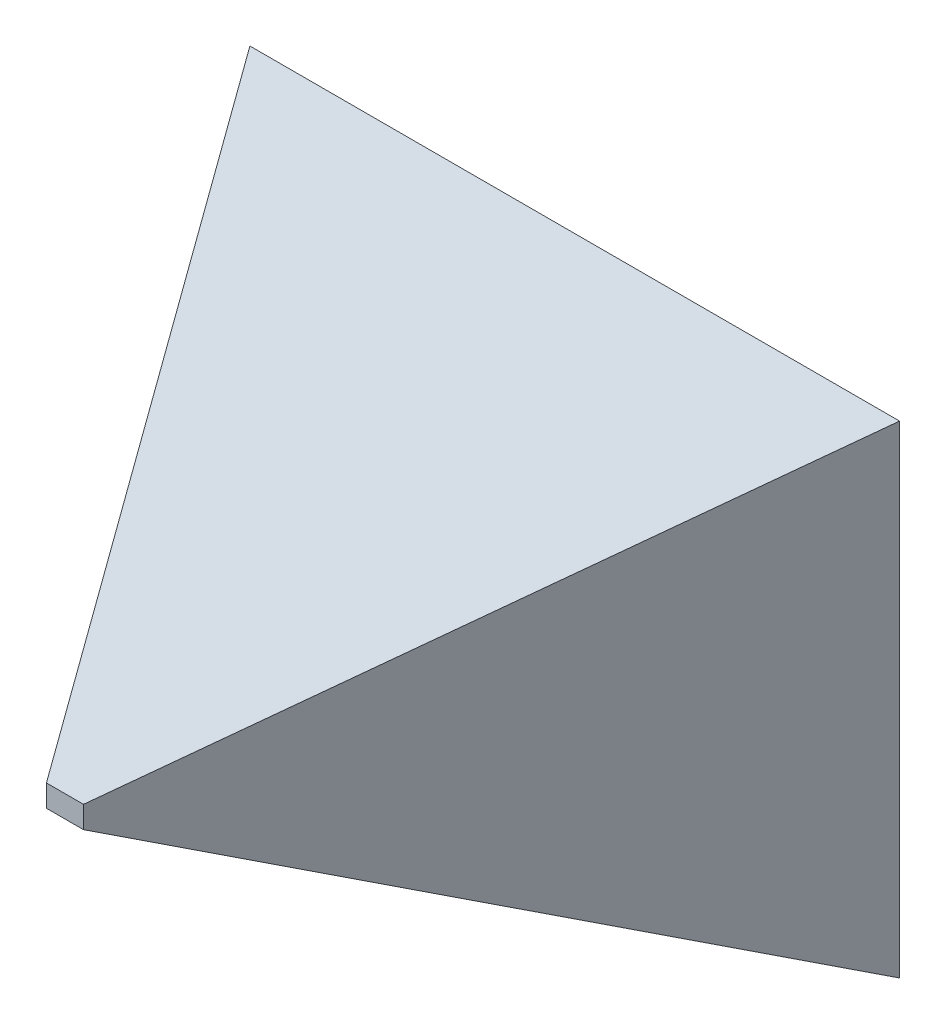
SolidWorks part; units mm, degrees
ref_plane "Front Plane" through (0, 0, 0) normal (0, 0, 1) x (1, 0, 0)
ref_plane "Top Plane" through (0, 0, 0) normal (0, 1, 0) x (1, 0, 0)
ref_plane "Right Plane" through (0, 0, 0) normal (1, 0, 0) x (0, 0, -1)
sketch "Sketch1" plane through (0, 0, 0) normal (0, 0, 1) x (1, 0, 0)
  line L1 (509.778, -378.46) -> (-509.778, -378.46)
  line L2 (509.778, -378.46) -> (509.778, 378.46)
  line L3 (509.778, 378.46) -> (-509.778, 378.46)
  line L4 (-509.778, -378.46) -> (-509.778, 378.46)
  line L5 (509.778, -378.46) -> (-509.778, 378.46) construction
  line L6 (509.778, 378.46) -> (-509.778, -378.46) construction
  point P0 (0, 0)
  dimension "D1" = 1019.556
  dimension "D2" = 756.92
extrude "Boss-Extrude1" add sketch "Sketch1" along normal blind 800
sketch "Sketch2" plane through (509.778, 0, 0) normal (1, 0, 0) x (0, 0, -1)
  line L0 (0, 378.46) -> (-838.196, 0)
  line L1 (-838.196, 0) -> (0, -378.46)
  line L2 (-838.196, 0) -> (0, 0) construction
  dimension "D1" = 48.6
extrude "Cut-Extrude1" cut sketch "Sketch2" against normal through all flip side to cut
sketch "Sketch4" plane through (0, 0, 0) normal (0, 1, 0) x (1, 0, 0)
  line L0 (0, 0) -> (0, -848.4131) construction
  line L1 (-509.778, 0) -> (0, -848.4131)
  line L2 (0, -848.4131) -> (509.778, 0)
  dimension "D1" = 62
extrude "Cut-Extrude2" cut sketch "Sketch4" against normal through all and the other way through all flip side to cut
